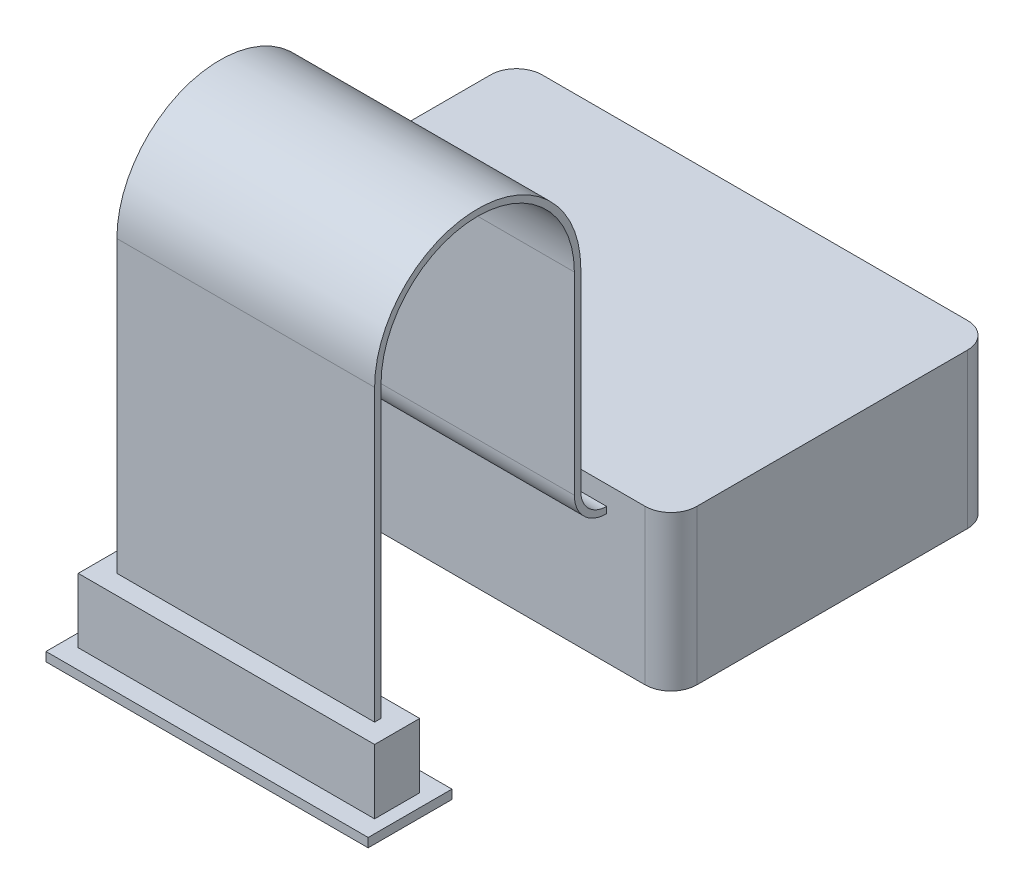
SolidWorks part; units mm, degrees
ref_plane "Front Plane" through (0, 0, 0) normal (0, 0, 1) x (1, 0, 0)
ref_plane "Top Plane" through (0, 0, 0) normal (0, 1, 0) x (1, 0, 0)
ref_plane "Right Plane" through (0, 0, 0) normal (1, 0, 0) x (0, 0, -1)
sketch "Sketch1" plane through (0, 0, 0) normal (0, 1, 0) x (1, 0, 0)
  line L1 (-46.99, 31.75) -> (46.99, 31.75)
  line L2 (-46.99, 31.75) -> (-46.99, -31.75)
  line L3 (-46.99, -31.75) -> (46.99, -31.75)
  line L4 (46.99, 31.75) -> (46.99, -31.75)
  line L5 (-46.99, 31.75) -> (46.99, -31.75) construction
  line L6 (-46.99, -31.75) -> (46.99, 31.75) construction
  point P0 (0, 0)
  dimension "D1" = 63.5
  dimension "D2" = 93.98
extrude "Boss-Extrude1" add sketch "Sketch1" along normal blind 30.48
fillet "Fillet1" radius 5.08 4 edges at (-46.99, 15.24, -31.75) (46.99, 15.24, -31.75) (46.99, 15.24, 31.75) (-46.99, 15.24, 31.75)
sketch "Sketch2" plane through (46.99, 0, 0) normal (1, 0, 0) x (0, 0, -1)
  line L0 (-31.75, 0) -> (-31.75, 30.48) construction
  line L1 (-38.1, 31.75) -> (-38.1, 69.85)
  line L2 (-76.2, 69.85) -> (-76.2, 0)
  line L3 (-76.2, 0) -> (-77.47, 0)
  line L4 (-26.67, 0) -> (26.67, 0) construction
  line L5 (-77.47, 0) -> (-77.47, 69.85)
  line L6 (-36.83, 69.85) -> (-36.83, 31.75)
  line L7 (-31.75, 26.67) -> (-31.75, 25.4)
  arc A0 (-38.1, 31.75) -> (-31.75, 25.4) centre (-31.75, 31.75) ccw
  arc A1 (-38.1, 69.85) -> (-76.2, 69.85) centre (-57.15, 69.85) ccw
  arc A2 (-36.83, 69.85) -> (-77.47, 69.85) centre (-57.15, 69.85) ccw
  arc A3 (-36.83, 31.75) -> (-31.75, 26.67) centre (-31.75, 31.75) ccw
  point P12 (-31.75, 25.4)
  dimension "D1" = 38.1
  dimension "D3" = 12.7
  dimension "D2" = 25.4
  dimension "D4" = 38.1
  dimension "D5" = 1.27
extrude "Boss-Extrude2" add sketch "Sketch2" against normal blind 50.8 from offset 12.7 offset against normal yes
sketch "Sketch4" plane through (0, 0, 0) normal (0, -1, 0) x (1, 0, 0)
  line L0 (-16.51, 76.2) -> (34.29, 76.2) construction
  line L1 (-22.86, 85.09) -> (40.64, 85.09)
  line L2 (-22.86, 85.09) -> (-22.86, 68.58)
  line L3 (-22.86, 68.58) -> (40.64, 68.58)
  line L4 (40.64, 85.09) -> (40.64, 68.58)
  line L5 (-22.86, 85.09) -> (40.64, 68.58) construction
  line L6 (-22.86, 68.58) -> (40.64, 85.09) construction
  line L7 (34.29, 77.47) -> (34.29, 76.2) construction
  point P0 (8.89, 76.835)
  point P5 (0, 0)
  point P8 (8.89, 76.2)
  point P9 (0, 0)
  point P12 (34.29, 76.835)
  dimension "D1" = 63.5
  dimension "D2" = 16.51
extrude "Boss-Extrude3" add sketch "Sketch4" along normal blind 1.778
sketch "Sketch5" plane through (0, 0, 0) normal (0, 1, 0) x (1, 0, 0)
  line L0 (-22.86, -85.09) -> (-22.86, -68.58) construction
  line L1 (-20.32, -72.39) -> (38.1, -72.39)
  line L2 (-20.32, -72.39) -> (-20.32, -81.28)
  line L3 (-20.32, -81.28) -> (38.1, -81.28)
  line L4 (38.1, -72.39) -> (38.1, -81.28)
  line L5 (-20.32, -72.39) -> (38.1, -81.28) construction
  line L6 (-20.32, -81.28) -> (38.1, -72.39) construction
  line L7 (40.64, -85.09) -> (-22.86, -85.09) construction
  point P0 (8.89, -76.835)
  point P5 (0, 0)
  point P8 (-22.86, -76.835)
  point P9 (0, 0)
  point P12 (8.89, -85.09)
  dimension "D1" = 8.89
  dimension "D2" = 58.42
extrude "Boss-Extrude4" add sketch "Sketch5" along normal blind 12.7
